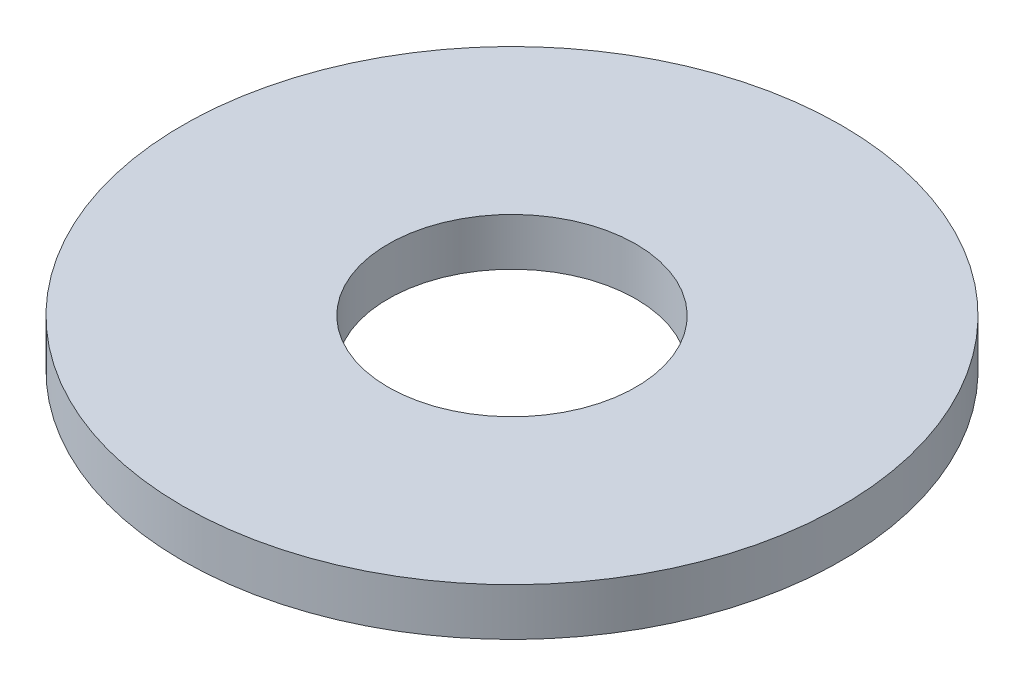
SolidWorks part; units mm, degrees
ref_plane "Front Plane" through (0, 0, 0) normal (0, 0, 1) x (1, 0, 0)
ref_plane "Top Plane" through (0, 0, 0) normal (0, 1, 0) x (1, 0, 0)
ref_plane "Right Plane" through (0, 0, 0) normal (1, 0, 0) x (0, 0, -1)
sketch "Sketch1" plane through (0, 0, 0) normal (0, 1, 0) x (1, 0, 0)
  circle A0 centre (0, 0) radius 3.175
  dimension "OD" = 6.35
extrude "Boss-Extrude1" add sketch "Sketch1" along normal blind 0.4572
sketch "Sketch5" plane through (0, 0.4572, 0) normal (0, 1, 0) x (-1, 0, 0)
  circle A0 centre (0, 0) radius 1.1938
  dimension "ID" = 2.3876
extrude "Cut-Extrude1" cut sketch "Sketch5" against normal through all
